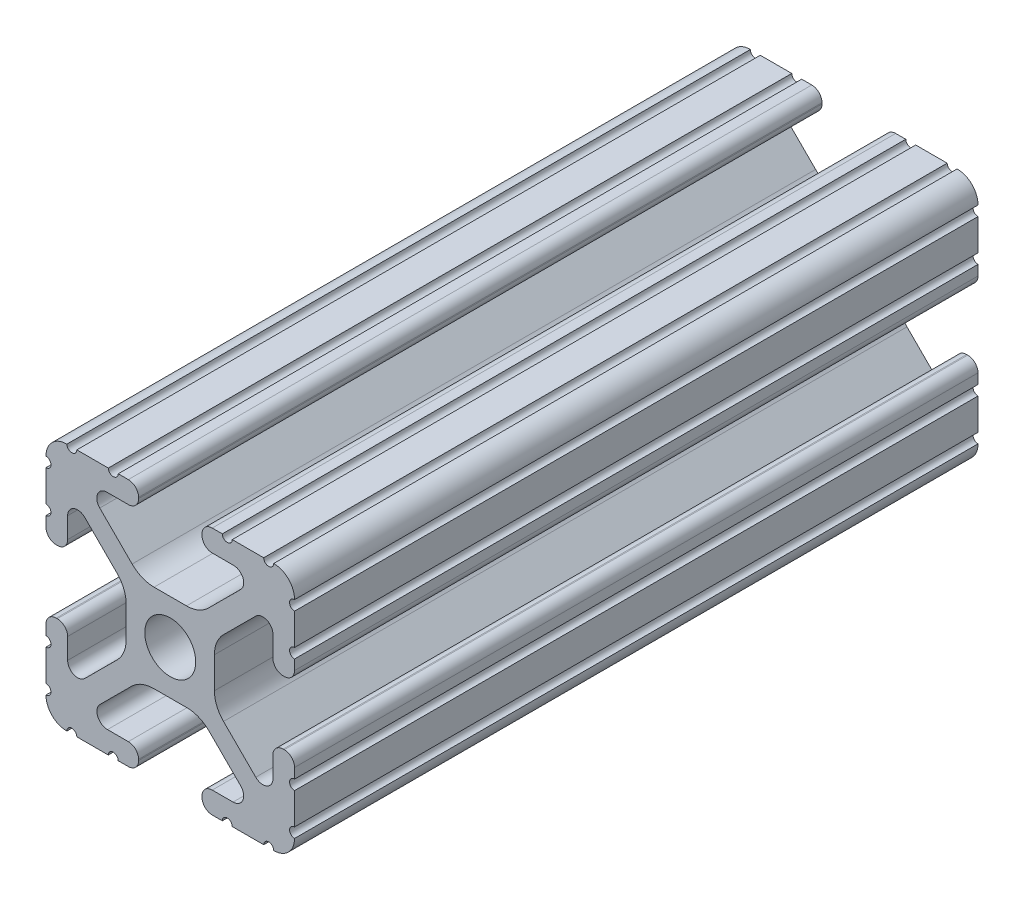
SolidWorks part; units mm, degrees
material "1060 Alloy"
ref_plane "Front Plane" through (0, 0, 0) normal (0, 0, 1) x (1, 0, 0)
ref_plane "Top Plane" through (0, 0, 0) normal (0, 1, 0) x (1, 0, 0)
ref_plane "Right Plane" through (0, 0, 0) normal (1, 0, 0) x (0, 0, -1)
sketch "Sketch1" plane through (0, 0, 0) normal (0, 0, 1) x (1, 0, 0)
  line L88 (-7.1797, -8.6452) -> (-3.9523, -5.4237)
  line L89 (-1.7093, -4.4958) -> (1.7093, -4.4958)
  line L90 (3.9523, -5.4237) -> (7.1797, -8.6452)
  line L91 (6.4164, -10.4902) -> (4.2875, -10.4902)
  line L92 (3.2385, -11.5392) -> (3.2385, -11.651)
  line L93 (4.2875, -12.7) -> (5.3171, -12.7)
  line L94 (6.3331, -12.7) -> (9.5504, -12.7)
  line L95 (12.7, -9.5504) -> (12.7, -6.3331)
  line L96 (12.7, -5.3171) -> (12.7, -4.2875)
  line L97 (11.651, -3.2385) -> (11.5392, -3.2385)
  line L98 (10.4902, -4.2875) -> (10.4902, -6.4021)
  line L99 (8.7371, -7.1294) -> (5.441, -3.8408)
  line L100 (4.5085, -1.5932) -> (4.5085, 1.5932)
  line L101 (5.441, 3.8408) -> (8.7371, 7.1294)
  line L102 (10.4902, 6.4021) -> (10.4902, 4.2875)
  line L103 (11.5392, 3.2385) -> (11.651, 3.2385)
  line L104 (12.7, 4.2875) -> (12.7, 5.3171)
  line L105 (12.7, 6.3331) -> (12.7, 9.5504)
  line L106 (9.5504, 12.7) -> (6.3331, 12.7)
  line L107 (5.3171, 12.7) -> (4.2875, 12.7)
  line L108 (3.2385, 11.651) -> (3.2385, 11.5392)
  line L109 (4.2875, 10.4902) -> (6.4768, 10.4902)
  line L110 (7.207, 8.7244) -> (3.8983, 5.4232)
  line L111 (1.6558, 4.4958) -> (-1.6558, 4.4958)
  line L112 (-3.8983, 5.4232) -> (-7.207, 8.7244)
  line L113 (-6.4768, 10.4902) -> (-4.2875, 10.4902)
  line L114 (-3.2385, 11.5392) -> (-3.2385, 11.651)
  line L115 (-4.2875, 12.7) -> (-5.3171, 12.7)
  line L116 (-6.3331, 12.7) -> (-9.5504, 12.7)
  line L117 (-12.7, 9.5504) -> (-12.7, 6.3331)
  line L118 (-12.7, 5.3171) -> (-12.7, 4.2875)
  line L119 (-11.651, 3.2385) -> (-11.5392, 3.2385)
  line L120 (-10.4902, 4.2875) -> (-10.4902, 6.4021)
  line L121 (-8.7371, 7.1294) -> (-5.441, 3.8408)
  line L122 (-4.5085, 1.5932) -> (-4.5085, -1.5932)
  line L123 (-5.441, -3.8408) -> (-8.7371, -7.1294)
  line L124 (-10.4902, -6.4021) -> (-10.4902, -4.2875)
  line L125 (-11.5392, -3.2385) -> (-11.651, -3.2385)
  line L126 (-12.7, -4.2875) -> (-12.7, -5.3171)
  line L127 (-12.7, -6.3331) -> (-12.7, -9.5504)
  line L128 (-9.5504, -12.7) -> (-6.3331, -12.7)
  line L129 (-5.3171, -12.7) -> (-4.2875, -12.7)
  line L130 (-3.2385, -11.651) -> (-3.2385, -11.5392)
  line L131 (-4.2875, -10.4902) -> (-6.4164, -10.4902)
  circle A1 centre (0, 0) radius 2.6035
  arc A104 (-7.1797, -8.6452) -> (-6.4164, -10.4902) centre (-6.4164, -9.4098) ccw
  arc A105 (-1.7093, -4.4958) -> (-3.9523, -5.4237) centre (-1.7093, -7.6708) ccw
  arc A106 (3.9523, -5.4237) -> (1.7093, -4.4958) centre (1.7093, -7.6708) ccw
  arc A107 (6.4164, -10.4902) -> (7.1797, -8.6452) centre (6.4164, -9.4098) ccw
  arc A108 (4.2875, -10.4902) -> (3.2385, -11.5392) centre (4.2875, -11.5392) ccw
  arc A109 (3.2385, -11.651) -> (4.2875, -12.7) centre (4.2875, -11.651) ccw
  arc A110 (6.3331, -12.7) -> (5.3171, -12.7) centre (5.8251, -12.7) ccw
  arc A111 (10.5664, -12.6998) -> (9.5504, -12.7) centre (10.0584, -12.7) ccw
  arc A112 (10.5664, -12.6998) -> (12.6998, -10.5664) centre (10.5918, -10.5918) ccw
  arc A113 (12.7, -9.5504) -> (12.6998, -10.5664) centre (12.7, -10.0584) ccw
  arc A114 (12.7, -5.3171) -> (12.7, -6.3331) centre (12.7, -5.8251) ccw
  arc A115 (12.7, -4.2875) -> (11.651, -3.2385) centre (11.651, -4.2875) ccw
  arc A116 (11.5392, -3.2385) -> (10.4902, -4.2875) centre (11.5392, -4.2875) ccw
  arc A117 (8.7371, -7.1294) -> (10.4902, -6.4021) centre (9.4628, -6.4021) ccw
  arc A118 (4.5085, -1.5932) -> (5.441, -3.8408) centre (7.6835, -1.5932) ccw
  arc A119 (5.441, 3.8408) -> (4.5085, 1.5932) centre (7.6835, 1.5932) ccw
  arc A120 (10.4902, 6.4021) -> (8.7371, 7.1294) centre (9.4628, 6.4021) ccw
  arc A121 (10.4902, 4.2875) -> (11.5392, 3.2385) centre (11.5392, 4.2875) ccw
  arc A122 (11.651, 3.2385) -> (12.7, 4.2875) centre (11.651, 4.2875) ccw
  arc A123 (12.7, 6.3331) -> (12.7, 5.3171) centre (12.7, 5.8251) ccw
  arc A124 (12.6998, 10.5664) -> (12.7, 9.5504) centre (12.7, 10.0584) ccw
  arc A125 (12.6998, 10.5664) -> (10.5664, 12.6998) centre (10.5918, 10.5918) ccw
  arc A126 (9.5504, 12.7) -> (10.5664, 12.6998) centre (10.0584, 12.7) ccw
  arc A127 (5.3171, 12.7) -> (6.3331, 12.7) centre (5.8251, 12.7) ccw
  arc A128 (4.2875, 12.7) -> (3.2385, 11.651) centre (4.2875, 11.651) ccw
  arc A129 (3.2385, 11.5392) -> (4.2875, 10.4902) centre (4.2875, 11.5392) ccw
  arc A130 (7.207, 8.7244) -> (6.4768, 10.4902) centre (6.4768, 9.4563) ccw
  arc A131 (1.6558, 4.4958) -> (3.8983, 5.4232) centre (1.6558, 7.6708) ccw
  arc A132 (-3.8983, 5.4232) -> (-1.6558, 4.4958) centre (-1.6558, 7.6708) ccw
  arc A133 (-6.4768, 10.4902) -> (-7.207, 8.7244) centre (-6.4768, 9.4563) ccw
  arc A134 (-4.2875, 10.4902) -> (-3.2385, 11.5392) centre (-4.2875, 11.5392) ccw
  arc A135 (-3.2385, 11.651) -> (-4.2875, 12.7) centre (-4.2875, 11.651) ccw
  arc A136 (-6.3331, 12.7) -> (-5.3171, 12.7) centre (-5.8251, 12.7) ccw
  arc A137 (-10.5664, 12.6998) -> (-9.5504, 12.7) centre (-10.0584, 12.7) ccw
  arc A138 (-10.5664, 12.6998) -> (-12.6998, 10.5664) centre (-10.5918, 10.5918) ccw
  arc A139 (-12.7, 9.5504) -> (-12.6998, 10.5664) centre (-12.7, 10.0584) ccw
  arc A140 (-12.7, 5.3171) -> (-12.7, 6.3331) centre (-12.7, 5.8251) ccw
  arc A141 (-12.7, 4.2875) -> (-11.651, 3.2385) centre (-11.651, 4.2875) ccw
  arc A142 (-11.5392, 3.2385) -> (-10.4902, 4.2875) centre (-11.5392, 4.2875) ccw
  arc A143 (-8.7371, 7.1294) -> (-10.4902, 6.4021) centre (-9.4628, 6.4021) ccw
  arc A144 (-4.5085, 1.5932) -> (-5.441, 3.8408) centre (-7.6835, 1.5932) ccw
  arc A145 (-5.441, -3.8408) -> (-4.5085, -1.5932) centre (-7.6835, -1.5932) ccw
  arc A146 (-10.4902, -6.4021) -> (-8.7371, -7.1294) centre (-9.4628, -6.4021) ccw
  arc A147 (-10.4902, -4.2875) -> (-11.5392, -3.2385) centre (-11.5392, -4.2875) ccw
  arc A148 (-11.651, -3.2385) -> (-12.7, -4.2875) centre (-11.651, -4.2875) ccw
  arc A149 (-12.7, -6.3331) -> (-12.7, -5.3171) centre (-12.7, -5.8251) ccw
  arc A150 (-12.6998, -10.5664) -> (-12.7, -9.5504) centre (-12.7, -10.0584) ccw
  arc A151 (-12.6998, -10.5664) -> (-10.5664, -12.6998) centre (-10.5918, -10.5918) ccw
  arc A152 (-9.5504, -12.7) -> (-10.5664, -12.6998) centre (-10.0584, -12.7) ccw
  arc A153 (-5.3171, -12.7) -> (-6.3331, -12.7) centre (-5.8251, -12.7) ccw
  arc A154 (-4.2875, -12.7) -> (-3.2385, -11.651) centre (-4.2875, -11.651) ccw
  arc A155 (-3.2385, -11.5392) -> (-4.2875, -10.4902) centre (-4.2875, -11.5392) ccw
extrude "Boss-Extrude1" add sketch "Sketch1" along normal mid plane 69.85
